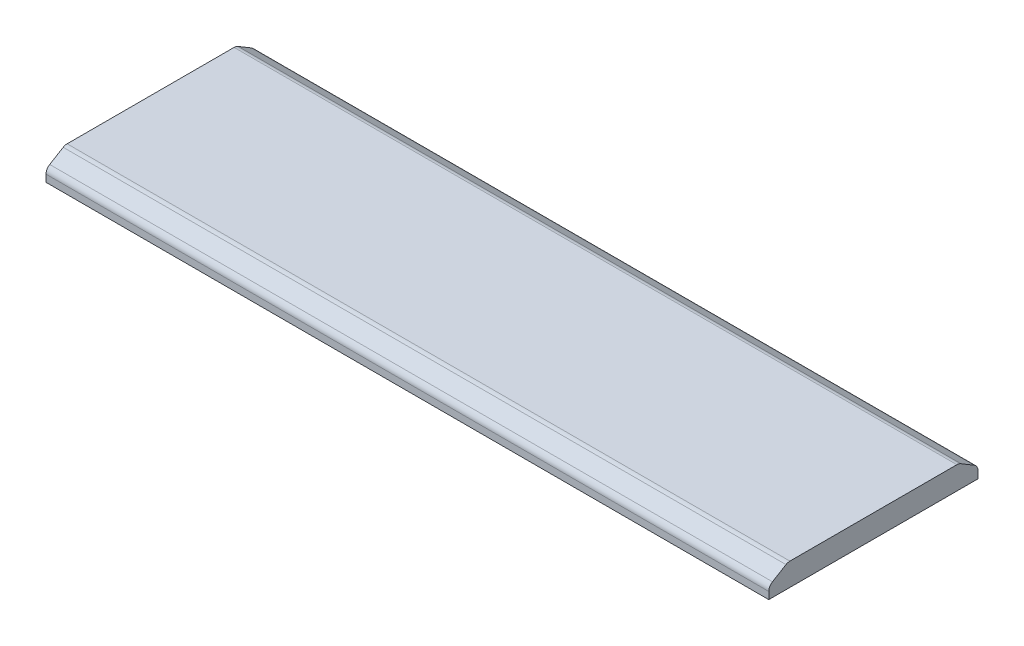
SolidWorks part; units mm, degrees
ref_plane "Front Plane" through (0, 0, 0) normal (0, 0, 1) x (1, 0, 0)
ref_plane "Top Plane" through (0, 0, 0) normal (0, 1, 0) x (1, 0, 0)
ref_plane "Right Plane" through (0, 0, 0) normal (1, 0, 0) x (0, 0, -1)
sketch "Sketch1" plane through (0, 0, 0) normal (1, 0, 0) x (0, 0, -1)
  line L0 (-22.5, 0) -> (22.5, 0)
  line L1 (22.5, 0) -> (27.5, -3)
  line L2 (27.5, -3) -> (27.5, -6)
  line L3 (27.5, -6) -> (-27.5, -6)
  line L4 (-27.5, -6) -> (-27.5, -3)
  line L5 (-27.5, -3) -> (-22.5, 0)
  point P3 (0, 0)
  dimension "D1" = 55
  dimension "D2" = 3
  dimension "D3" = 3
  dimension "D4" = 3
  dimension "D5" = 45
extrude "Boss-Extrude1" add sketch "Sketch1" along normal blind 190
fillet "Fillet1" radius 2 4 edges at (95, -3, 27.5) (95, 0, 22.5) (95, -3, -27.5) (95, 0, -22.5)
sketch "Sketch2" plane through (0, -6, 0) normal (0, -1, 0) x (1, 0, 0)
  line L0 (190, -27.5) -> (0, -27.5) construction
  line L5 (30, -19.5) -> (34, -19.5)
  line L6 (30, -19.5) -> (30, -22.5)
  line L7 (30, -22.5) -> (34, -22.5)
  line L8 (34, -19.5) -> (34, -22.5)
  line L9 (0, 27.5) -> (0, -27.5) construction
  line L10 (0, 0) -> (35.5146, 0) construction
  line L11 (49, -27.5) -> (49, -15.8941) construction
  line L12 (95, -27.5) -> (95, -15.8941) construction
  line L13 (30, 22.5) -> (34, 22.5)
  line L14 (34, 19.5) -> (34, 22.5)
  line L15 (30, 19.5) -> (34, 19.5)
  line L16 (30, 19.5) -> (30, 22.5)
  line L17 (68, -22.5) -> (64, -22.5)
  line L18 (64, -19.5) -> (64, -22.5)
  line L19 (68, -19.5) -> (64, -19.5)
  line L20 (68, -19.5) -> (68, -22.5)
  line L21 (68, 19.5) -> (68, 22.5)
  line L22 (68, 19.5) -> (64, 19.5)
  line L23 (64, 19.5) -> (64, 22.5)
  line L24 (68, 22.5) -> (64, 22.5)
  line L25 (160, -22.5) -> (156, -22.5)
  line L26 (156, -19.5) -> (156, -22.5)
  line L27 (160, -19.5) -> (156, -19.5)
  line L28 (160, -19.5) -> (160, -22.5)
  line L29 (122, -19.5) -> (122, -22.5)
  line L30 (122, -19.5) -> (126, -19.5)
  line L31 (126, -19.5) -> (126, -22.5)
  line L32 (122, -22.5) -> (126, -22.5)
  line L33 (122, 19.5) -> (126, 19.5)
  line L34 (126, 19.5) -> (126, 22.5)
  line L35 (122, 22.5) -> (126, 22.5)
  line L36 (122, 19.5) -> (122, 22.5)
  line L37 (160, 19.5) -> (160, 22.5)
  line L38 (160, 19.5) -> (156, 19.5)
  line L39 (156, 19.5) -> (156, 22.5)
  line L40 (160, 22.5) -> (156, 22.5)
  dimension "D1" = 5
  dimension "D2" = 30
  dimension "D3" = 4
  dimension "D4" = 3
  dimension "D5" = 15
extrude "Boss-Extrude2" add sketch "Sketch2" along normal blind 2
sketch "Sketch3" plane through (0, -8, 0) normal (0, -1, 0) x (1, 0, 0)
  line L0 (30, -19.5) -> (30, -22.5) construction
  line L1 (30, -19.5) -> (34, -19.5)
  line L2 (30, -19.5) -> (30, -24.5)
  line L3 (30, -24.5) -> (34, -24.5)
  line L4 (34, -19.5) -> (34, -24.5)
  line L5 (30, -19.5) -> (30, -22.5) construction
  line L6 (34, -22.5) -> (34, -19.5) construction
  line L7 (30, -22.5) -> (34, -22.5) construction
  line L8 (34, -19.5) -> (30, -19.5) construction
  line L9 (0, 0) -> (19.8451, 0) construction
  line L10 (95, -27.5) -> (95, -4.7727) construction
  line L11 (190, -27.5) -> (0, -27.5) construction
  line L12 (49, -27.5) -> (49, -9.4806) construction
  line L13 (30, 24.5) -> (34, 24.5)
  line L14 (34, 19.5) -> (34, 24.5)
  line L15 (30, 19.5) -> (34, 19.5)
  line L16 (30, 19.5) -> (30, 24.5)
  line L17 (68, -24.5) -> (64, -24.5)
  line L18 (64, -19.5) -> (64, -24.5)
  line L19 (68, -19.5) -> (64, -19.5)
  line L20 (68, -19.5) -> (68, -24.5)
  line L21 (68, 19.5) -> (68, 24.5)
  line L22 (68, 19.5) -> (64, 19.5)
  line L23 (64, 19.5) -> (64, 24.5)
  line L24 (68, 24.5) -> (64, 24.5)
  line L25 (160, -24.5) -> (156, -24.5)
  line L26 (156, -19.5) -> (156, -24.5)
  line L27 (160, -19.5) -> (156, -19.5)
  line L28 (160, -19.5) -> (160, -24.5)
  line L29 (122, -19.5) -> (122, -24.5)
  line L30 (122, -19.5) -> (126, -19.5)
  line L31 (126, -19.5) -> (126, -24.5)
  line L32 (122, -24.5) -> (126, -24.5)
  line L33 (122, 19.5) -> (126, 19.5)
  line L34 (126, 19.5) -> (126, 24.5)
  line L35 (122, 24.5) -> (126, 24.5)
  line L36 (122, 19.5) -> (122, 24.5)
  line L37 (160, 19.5) -> (160, 24.5)
  line L38 (160, 19.5) -> (156, 19.5)
  line L39 (156, 19.5) -> (156, 24.5)
  line L40 (160, 24.5) -> (156, 24.5)
  dimension "D1" = 2
  dimension "D2" = 15
extrude "Boss-Extrude3" add sketch "Sketch3" along normal blind 3
sketch "Sketch4" plane through (0, 0, 0) normal (-1, 0, 0) x (0, 0, 1)
  line L0 (-24.5, -8) -> (-21.3, -11)
  line L1 (-24.5, -8) -> (-24.5, -11)
  line L2 (-21.3, -11) -> (-24.5, -11)
  line L4 (0, -6) -> (0, -8) construction
  line L5 (27.5, -6) -> (-27.5, -6) construction
  line L6 (24.5, -8) -> (21.3, -11)
  line L7 (21.3, -11) -> (24.5, -11)
  line L8 (24.5, -8) -> (24.5, -11)
  dimension "D1" = 3.2
  dimension "D2" = 2
extrude "Cut-Extrude2" cut sketch "Sketch4" against normal through all
fillet "Fillet2" radius 1 8 edges at (158, -11, -19.5) (158, -11, 19.5) (124, -11, 19.5) (124, -11, -19.5) (66, -11, 19.5) (32, -11, 19.5) (66, -11, -19.5) (32, -11, -19.5)
fillet "Fillet3" radius 1 24 edges at (34, -6, -21) (32, -6, -19.5) (30, -6, -21) (64, -6, -21) (66, -6, -19.5) (68, -6, -21) (126, -6, -21) (122, -6, -21) (124, -6, -19.5) (156, -6, -21) (158, -6, -19.5) (160, -6, -21) (160, -6, 21) (158, -6, 19.5) (156, -6, 21) (126, -6, 21) (124, -6, 19.5) (122, -6, 21) (68, -6, 21) (66, -6, 19.5) (64, -6, 21) (34, -6, 21) (30, -6, 21) (32, -6, 19.5)
